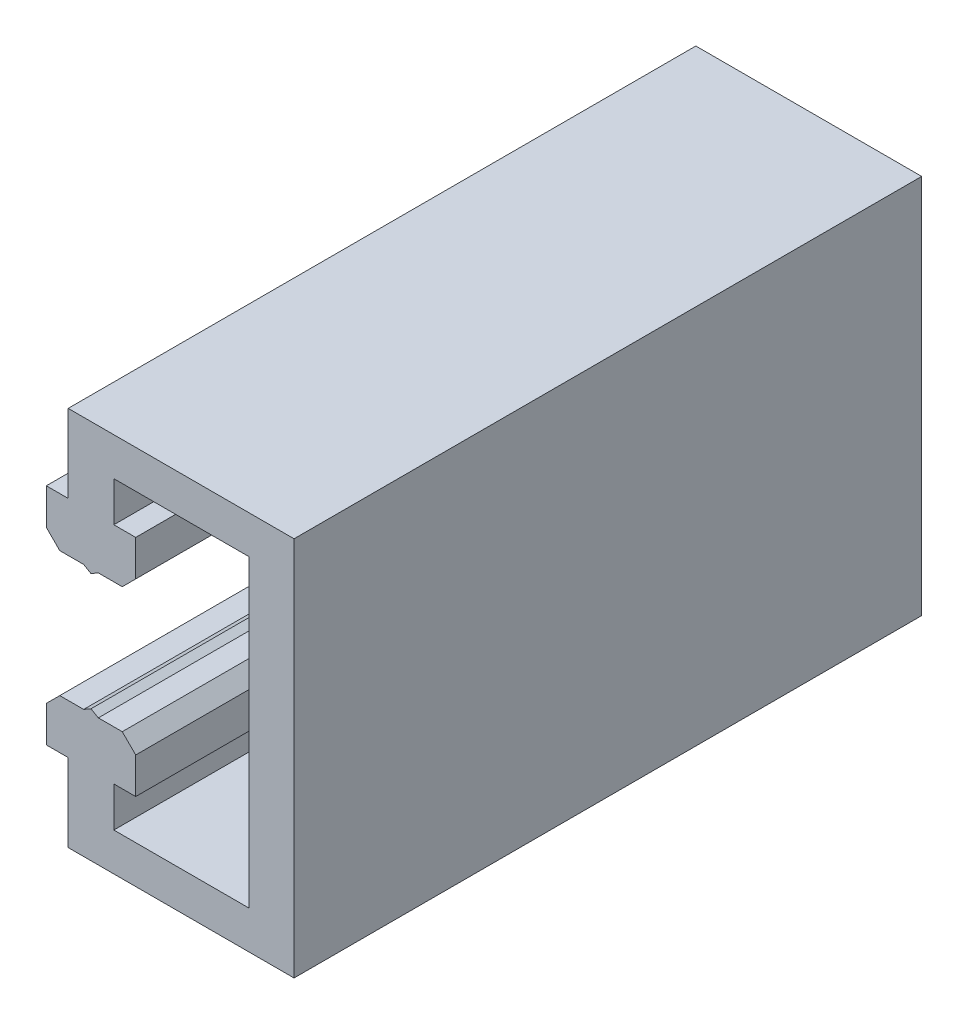
SolidWorks part; units mm, degrees
ref_plane "Front Plane" through (0, 0, 0) normal (0, 0, 1) x (1, 0, 0)
ref_plane "Top Plane" through (0, 0, 0) normal (0, 1, 0) x (1, 0, 0)
ref_plane "Right Plane" through (0, 0, 0) normal (1, 0, 0) x (0, 0, -1)
sketch "Sketch3" plane through (0, 0, 0) normal (0, 0, 1) x (1, 0, 0)
  line L0 (1253.633, 553.9424) -> (1265.5081, 553.9424)
  line L1 (1265.5081, 553.9424) -> (1265.5081, 533.9424)
  line L2 (1265.5081, 533.9424) -> (1253.633, 533.9424)
  line L3 (1253.633, 533.9424) -> (1253.633, 538.0424)
  line L4 (1253.633, 538.0424) -> (1252.483, 538.0424)
  line L5 (1252.483, 538.0424) -> (1252.483, 539.9353)
  line L6 (1252.483, 539.9353) -> (1253.1902, 540.6424)
  line L7 (1253.1902, 540.6424) -> (1254.4475, 540.6424)
  line L8 (1254.4475, 540.6424) -> (1254.8331, 540.8651)
  line L9 (1254.8331, 540.8651) -> (1255.2187, 540.6424)
  line L10 (1255.2187, 540.6424) -> (1256.4759, 540.6424)
  line L11 (1256.4759, 540.6424) -> (1257.1831, 539.9353)
  line L12 (1257.1831, 539.9353) -> (1257.1831, 538.0424)
  line L13 (1257.1831, 538.0424) -> (1256.0331, 538.0424)
  line L14 (1256.0331, 538.0424) -> (1256.0331, 535.9424)
  line L15 (1256.0331, 535.9424) -> (1263.1269, 535.9424)
  line L16 (1263.1269, 535.9424) -> (1263.1269, 551.9424)
  line L17 (1263.1269, 551.9424) -> (1256.0331, 551.9424)
  line L18 (1256.0331, 551.9424) -> (1256.0331, 549.8424)
  line L19 (1256.0331, 549.8424) -> (1257.1831, 549.8424)
  line L20 (1257.1831, 549.8424) -> (1257.1831, 547.9495)
  line L21 (1257.1831, 547.9495) -> (1256.4759, 547.2424)
  line L22 (1256.4759, 547.2424) -> (1255.2187, 547.2424)
  line L23 (1255.2187, 547.2424) -> (1254.8331, 547.0197)
  line L24 (1254.8331, 547.0197) -> (1254.4475, 547.2424)
  line L25 (1254.4475, 547.2424) -> (1253.1902, 547.2424)
  line L26 (1253.1902, 547.2424) -> (1252.483, 547.9495)
  line L27 (1252.483, 547.9495) -> (1252.483, 549.8424)
  line L28 (1252.483, 549.8424) -> (1253.633, 549.8424)
  line L29 (1253.633, 549.8424) -> (1253.633, 553.9424)
extrude "Boss-Extrude1" add sketch "Sketch3" along normal blind 33
